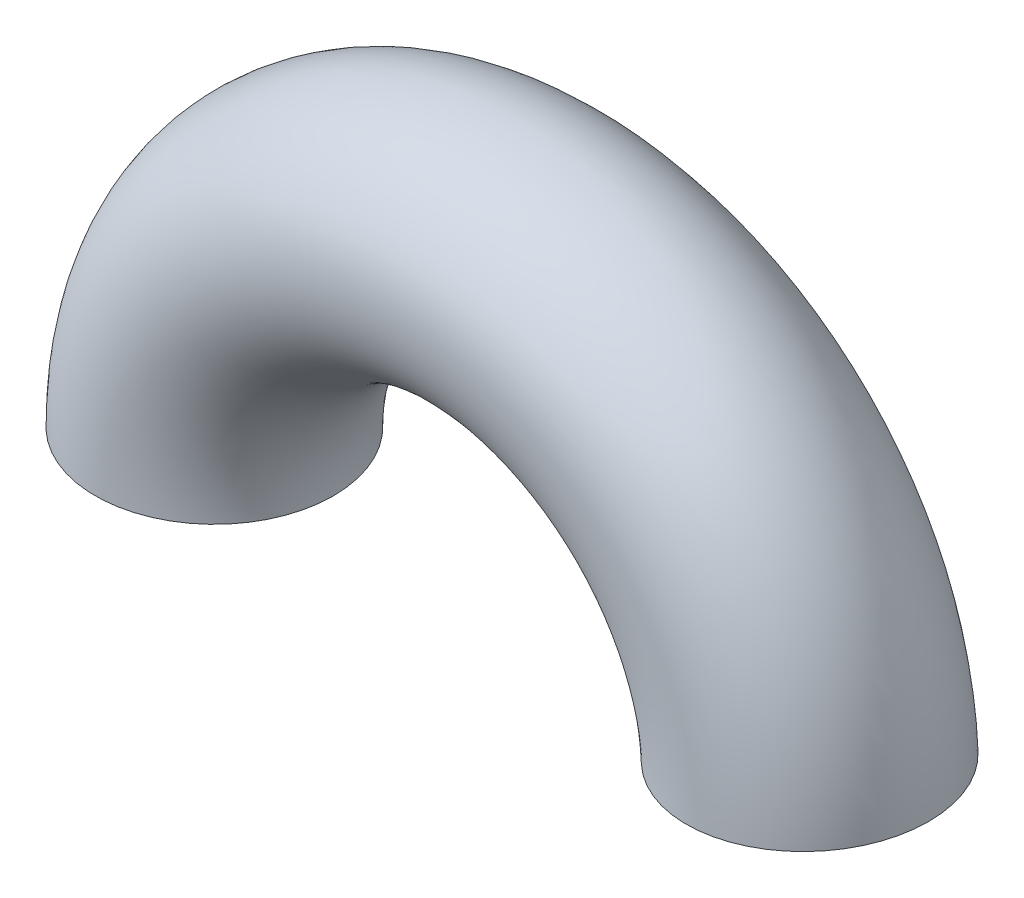
SolidWorks part; units mm, degrees
ref_plane "Front Plane" through (0, 0, 0) normal (0, 0, 1) x (1, 0, 0)
ref_plane "Top Plane" through (0, 0, 0) normal (0, 1, 0) x (1, 0, 0)
ref_plane "Right Plane" through (0, 0, 0) normal (1, 0, 0) x (0, 0, -1)
sketch "Sketch2" plane through (0, 0, 0) normal (0, 1, 0) x (1, 0, 0)
  circle A0 centre (0, 0) radius 5
  dimension "D1" = 10
sketch "Sketch3" plane through (0, 0, 0) normal (0, 0, 1) x (1, 0, 0)
  arc A0 (0, 0) -> (24.9913, 0.467) centre (12.5, 0) cw
  dimension "D1" = 12.5
sweep "Sweep1" add profiles "Sketch2" path "Sketch3"
shell "Shell1" thickness 0.5
